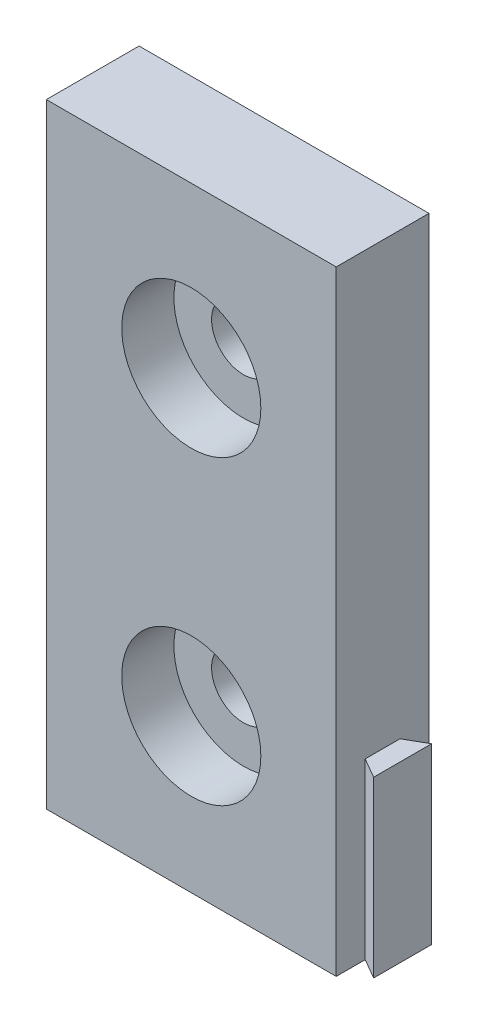
SolidWorks part; units mm, degrees
ref_plane "Front Plane" through (0, 0, 0) normal (0, 0, 1) x (1, 0, 0)
ref_plane "Top Plane" through (0, 0, 0) normal (0, 1, 0) x (1, 0, 0)
ref_plane "Right Plane" through (0, 0, 0) normal (1, 0, 0) x (0, 0, -1)
sketch "Sketch2" plane through (0, 0, 0) normal (0, 0, 1) x (1, 0, 0)
  line L0 (12.5, 53) -> (12.5, -45.5968) construction
  line L1 (0, 0) -> (25, 0)
  line L2 (0, 0) -> (0, 53)
  line L3 (0, 53) -> (25, 53)
  line L4 (25, 0) -> (25, 53)
  line L5 (0, 26.2) -> (42.3407, 26.2) construction
  circle A0 centre (12.5, 39.2) radius 2.75
  circle A1 centre (12.5, 13.2) radius 2.75
  dimension "D3" = 5.5
  dimension "D4" = 13
  dimension "D1" = 53
  dimension "D2" = 25
  dimension "D5" = 13
  dimension "D6" = 26.2
extrude "Boss-Extrude1" add sketch "Sketch2" along normal blind 8
sketch "Sketch3" plane through (0, 0, 0) normal (0, -1, 0) x (1, 0, 0)
  line L0 (25, 2.5) -> (26.7321, 1.5)
  line L1 (26.7321, 1.5) -> (26.7321, 6.5)
  line L2 (26.7321, 6.5) -> (25, 5.5)
  line L3 (25, 8) -> (25, 0) construction
  line L4 (25, 2.5) -> (25, 5.5)
  point P11 (25, 4)
  point P12 (25, 4)
  dimension "D1" = 60
  dimension "D2" = 60
  dimension "D3" = 5
  dimension "D4" = 3
extrude "Boss-Extrude2" add sketch "Sketch3" against normal blind 15
sketch "Sketch4" plane through (0, 0, 8) normal (0, 0, 1) x (1, 0, 0)
  circle A0 centre (12.5, 39.2) radius 6
  circle A1 centre (12.5, 13.2) radius 6
  dimension "D1" = 12
extrude "Cut-Extrude1" cut sketch "Sketch4" against normal blind 4.5
